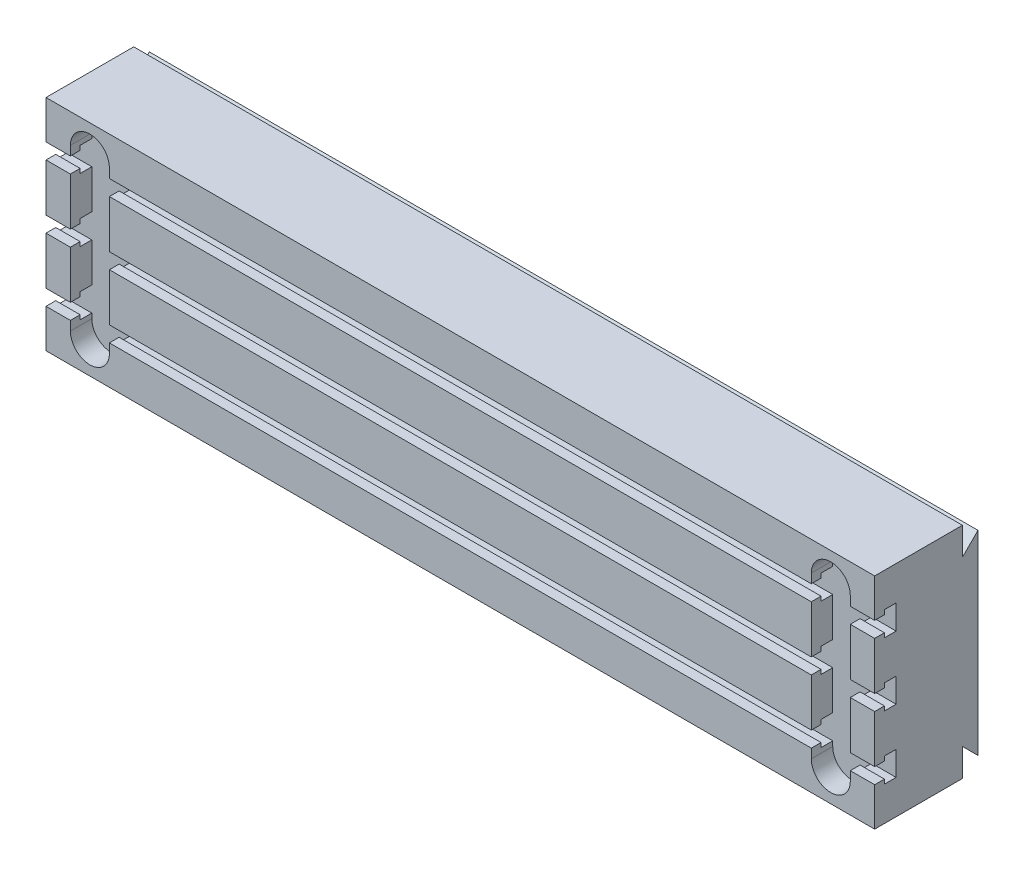
SolidWorks part; units mm, degrees
ref_plane "Front Plane" through (0, 0, 0) normal (1, 0, 0) x (0, 1, 0)
ref_plane "Top Plane" through (0, 0, 0) normal (0, 0, 1) x (0, 1, 0)
ref_plane "Right Plane" through (0, 0, 0) normal (0, 1, 0) x (-1, 0, 0)
sketch "Sketch1" plane through (0, 0, 0) normal (1, 0, 0) x (0, 1, 0)
  line L0 (84, -45) -> (100, -61)
  line L1 (-112.5, 45) -> (112.5, 45)
  line L2 (-112.5, 45) -> (-112.5, -45)
  line L3 (-112.5, -45) -> (112.5, -45)
  line L4 (112.5, 45) -> (112.5, -45)
  line L5 (0, -45) -> (0, 45) construction
  line L6 (-112.5, 0) -> (112.5, 0) construction
  line L7 (100, -61) -> (-100, -61)
  line L8 (-100, -61) -> (-84, -45)
  point P0 (0, 0)
  point P6 (0, -61)
  dimension "D1" = 225
  dimension "D2" = 90
  dimension "D3" = 200
  dimension "D4" = 45
  dimension "D5" = 16
extrude "Boss-Extrude1" add sketch "Sketch1" along normal mid plane 850 contours L8 L7 L0 L3 | L4 L1 L2 L3
sketch "Sketch2" plane through (0, 0, 0) normal (1, 0, 0) x (0, 1, 0)
  line L0 (-8, 45) -> (-8, 35)
  line L1 (-112.5, 45) -> (112.5, 45) construction
  line L2 (-8, 35) -> (-12.5, 35)
  line L3 (-12.5, 35) -> (-12.5, 23)
  line L4 (-12.5, 23) -> (12.5, 23)
  line L5 (12.5, 23) -> (12.5, 35)
  line L6 (12.5, 35) -> (8, 35)
  line L7 (8, 35) -> (8, 45)
  line L8 (8, 45) -> (-8, 45)
  point P4 (8.0767, 23.9398)
  point P12 (-10.2795, 45)
  point P13 (-23.2512, 33.7298)
  point P14 (0, 23)
  dimension "D1" = 25
  dimension "D2" = 16
  dimension "D3" = 10
  dimension "D4" = 12
extrude "Cut-Extrude1" cut sketch "Sketch2" against normal through all both and the other way through all
pattern_linear "LPattern1" count 2 spacing 65 along (0, 1, 0) count 2 spacing 65 along (0, -1, 0) of "Cut-Extrude1"
sketch "Sketch3" plane through (0, 0, 45) normal (0, 0, 1) x (1, 0, 0)
  line L0 (380, 82.5) -> (380, -82.5) construction
  line L1 (400, 82.5) -> (400, -82.5)
  line L2 (360, 82.5) -> (360, -82.5)
  line L3 (425, 100) -> (425, -100) construction
  line L4 (0, -58.3) -> (0, 58.3) construction
  line L5 (-380, 82.5) -> (-380, -82.5) construction
  line L6 (-400, 82.5) -> (-400, -82.5)
  line L7 (-360, 82.5) -> (-360, -82.5)
  arc A0 (400, 82.5) -> (360, 82.5) centre (380, 82.5) ccw
  arc A1 (360, -82.5) -> (400, -82.5) centre (380, -82.5) ccw
  arc A2 (-400, 82.5) -> (-360, 82.5) centre (-380, 82.5) cw
  arc A3 (-360, -82.5) -> (-400, -82.5) centre (-380, -82.5) cw
  point P2 (380, 0)
  point P7 (0, 0)
  point P15 (-380, 0)
  dimension "D2" = 40
  dimension "D1" = 45
  dimension "D3" = 165
extrude "Cut-Extrude2" cut sketch "Sketch3" against normal up to surface and the other way through all up to face at (0, 0, 23)
